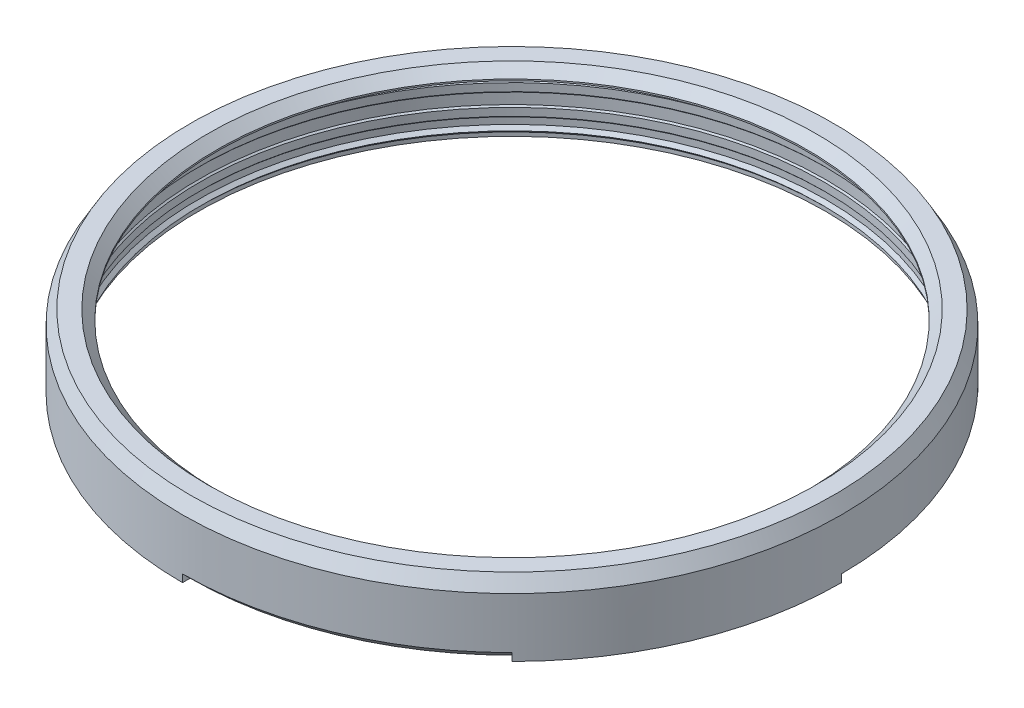
SolidWorks part; units mm, degrees
ref_plane "前视基准面" through (0, 0, 0) normal (0, 0, 1) x (1, 0, 0)
ref_plane "上视基准面" through (0, 0, 0) normal (0, 1, 0) x (1, 0, 0)
ref_plane "右视基准面" through (0, 0, 0) normal (1, 0, 0) x (0, 0, -1)
sketch "草图1" plane through (0, 0, 0) normal (0, 1, 0) x (1, 0, 0)
  circle A0 centre (0, 0) radius 43
  dimension "D1" = 86
extrude "凸台-拉伸1" add sketch "草图1" along normal blind 2
sketch "草图2" plane through (0, 0, 0) normal (-0.8788, 0, 0.4772) x (0.4772, 0, 0.8788)
  line L0 (40.93, -8) -> (40.93, -7.5)
  line L1 (40.93, -7.5) -> (40.505, -7.075)
  line L2 (40.505, -7.075) -> (40.93, -6.65)
  line L3 (40.93, -6.65) -> (40.93, -5.8)
  line L4 (40.93, -5.8) -> (40.74, -5.61)
  line L5 (40.74, -5.61) -> (40.74, -4.59)
  line L6 (40.74, -4.59) -> (40.93, -4.4)
  line L7 (40.93, -4.4) -> (40.93, -3)
  line L8 (40.93, -3) -> (40.74, -2.81)
  line L9 (40.74, -2.81) -> (40.74, -1.79)
  line L10 (40.74, -1.79) -> (40.93, -1.6)
  line L11 (40.93, -1.6) -> (40.93, -1.4)
  line L12 (39.53, 0) -> (43, 0)
  line L13 (43, 0) -> (43, -8)
  line L14 (43, -8) -> (40.93, -8)
  line L15 (40.8, -8) -> (42, -8) construction
  line L16 (40.8, -8) -> (40.8, -7.5) construction
  line L17 (0, 0) -> (0, 21.0059) construction
  arc A0 (40.93, -1.4) -> (39.53, 0) centre (39.53, -1.4) ccw
  dimension "D9" = 1.4
  dimension "D1" = 2.26
  dimension "D2" = 8
  dimension "D3" = 0.5
  dimension "D4" = 0.85
  dimension "D5" = 1.4
  dimension "D6" = 1.02
  dimension "D7" = 1.02
  dimension "D8" = 0.2
  dimension "D10" = 135
  dimension "D11" = 0.13
revolve "旋转1" add sketch "草图2" angle 360 about L17
sketch "草图3" plane through (0, 2, 0) normal (0, 1, 0) x (1, 0, 0)
  circle A0 centre (0, 0) radius 38.5
  circle A1 centre (0, 0) radius 43 construction
  dimension "D1" = 4.5
extrude "切除-拉伸1" cut sketch "草图3" against normal through all
sketch "草图4" plane through (0, 2, 0) normal (0, 1, 0) x (1, 0, 0)
  circle A1 centre (0, 0) radius 43
  circle A2 centre (0, 0) radius 43
  dimension "D1" = 0
sketch "草图5" plane through (0, 2, 0) normal (0, 1, 0) x (1, 0, 0)
  circle A1 centre (0, 0) radius 43
  circle A2 centre (0, 0) radius 43
  dimension "D1" = 0
extrude "切除-拉伸3" cut sketch "草图5" against normal blind 0.6
chamfer "倒角1" distance 1.2 angle 45 1 edges at (0, 1.4, 38.5)
chamfer "倒角2" distance 1.732 angle 30 1 edges at (0, 1.4, 43)
sketch "草图6" plane through (0, 0, 0) normal (0, 0, 1) x (1, 0, 0)
  line L0 (43, -8) -> (43, -7)
  line L1 (43, -8) -> (43, -0.332) construction
  line L2 (43, -7) -> (42, -8)
  line L3 (-43, -8) -> (43, -8) construction
  line L4 (42, -8) -> (43, -8)
  line L5 (0, 0) -> (0, 8.5489) construction
  dimension "D1" = 1
  dimension "D2" = 1
revolve "切除-旋转1" cut sketch "草图6" angle 45 about L5
pattern_circular "阵列(圆周)1" count 4 over 360 about axis through (0, 0, 0) along (0, 1, 0) of "切除-旋转1"
sketch "草图7" plane through (0, 0, 0) normal (0, -1, 0) x (1, 0, 0)
  circle A0 centre (0, 0) radius 39.32
  circle A1 centre (0, 0) radius 39.78
  circle A2 centre (0, 0) radius 38.5 construction
  dimension "D1" = 0.82
  dimension "D2" = 0.46
extrude "凸台-拉伸2" add sketch "草图7" along normal blind 0.5
